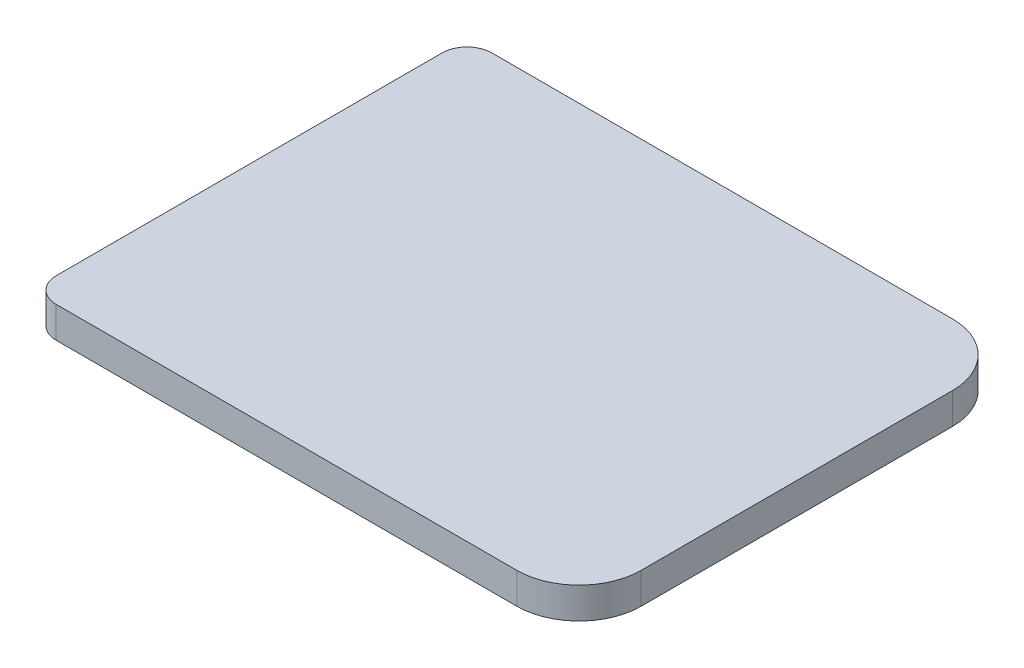
SolidWorks part; units mm, degrees
ref_plane "Front Plane" through (0, 0, 0) normal (0, 0, 1) x (1, 0, 0)
ref_plane "Top Plane" through (0, 0, 0) normal (0, 1, 0) x (1, 0, 0)
ref_plane "Right Plane" through (0, 0, 0) normal (1, 0, 0) x (0, 0, -1)
sketch "Sketch1" plane through (0, 0, 0) normal (0, 1, 0) x (1, 0, 0)
  line L1 (1.27, 0) -> (24.765, 0)
  line L2 (0, 1.27) -> (0, 20.955)
  line L3 (1.27, 22.225) -> (24.765, 22.225)
  line L4 (27.94, 3.175) -> (27.94, 19.05)
  arc A0 (24.765, 0) -> (27.94, 3.175) centre (24.765, 3.175) ccw
  arc A1 (24.765, 22.225) -> (27.94, 19.05) centre (24.765, 19.05) cw
  arc A2 (1.27, 0) -> (0, 1.27) centre (1.27, 1.27) cw
  arc A3 (0, 20.955) -> (1.27, 22.225) centre (1.27, 20.955) cw
  dimension "D3" = 3.175
  dimension "D1" = 1.27
  dimension "D2" = 27.94
  dimension "D4" = 22.225
extrude "Boss-Extrude1" add sketch "Sketch1" along normal blind 1.5875 contours L2 A3 L3 A1 L4 A0 L1 A2
